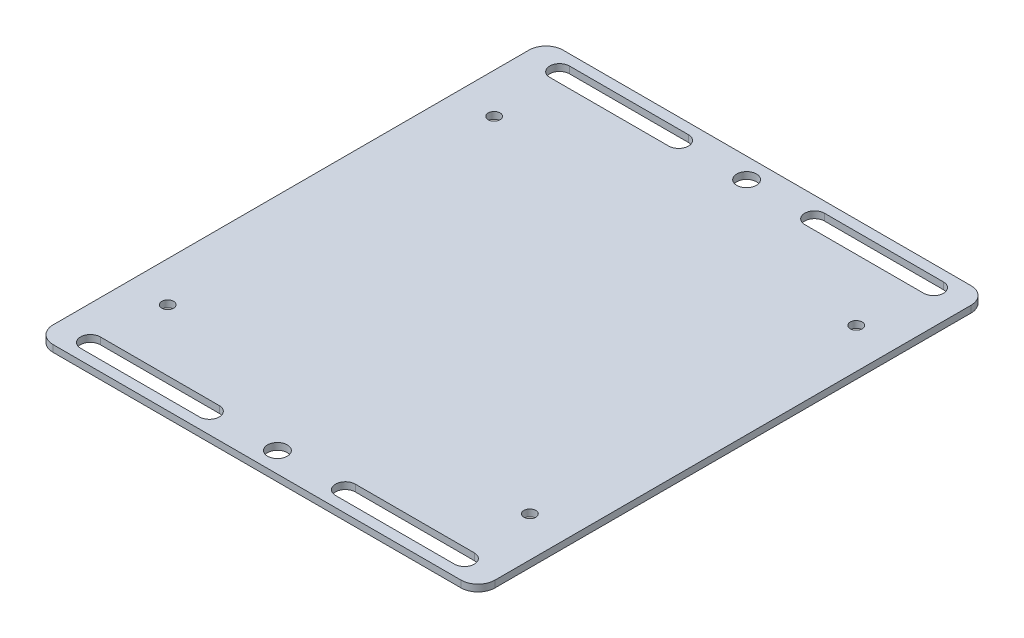
SolidWorks part; units mm, degrees
ref_plane "Front Plane" through (0, 0, 0) normal (0, 0, 1) x (1, 0, 0)
ref_plane "Top Plane" through (0, 0, 0) normal (0, 1, 0) x (1, 0, 0)
ref_plane "Right Plane" through (0, 0, 0) normal (1, 0, 0) x (0, 0, -1)
sketch "Sketch1" plane through (0, 0, 0) normal (0, 1, 0) x (1, 0, 0)
  line L1 (-57.5, 52.05) -> (57.5, 52.05) construction
  line L2 (-57.5, 52.05) -> (-57.5, -52.05) construction
  line L3 (-57.5, -52.05) -> (57.5, -52.05) construction
  line L4 (57.5, 52.05) -> (57.5, -52.05) construction
  line L5 (-57.5, 52.05) -> (57.5, -52.05) construction
  line L6 (-57.5, -52.05) -> (57.5, 52.05) construction
  line L7 (-65, -75) -> (65, -75)
  line L8 (-65, -75) -> (-65, 75)
  line L9 (-65, 75) -> (65, 75)
  line L10 (65, -75) -> (65, 75)
  line L11 (-65, -75) -> (65, 75) construction
  line L12 (-65, 75) -> (65, -75) construction
  point P0 (0, 0)
  point P6 (0, 0)
  dimension "D1" = 115
  dimension "D2" = 104.1
  dimension "D3" = 150
  dimension "D4" = 130
extrude "Boss-Extrude1" add sketch "Sketch1" along normal blind 2
sketch "Sketch2" plane through (0, 2, 0) normal (0, 1, 0) x (1, 0, 0)
  line L0 (-65, 69) -> (65, 69) construction
  line L1 (-65, 75) -> (-65, -75) construction
  line L2 (65, -75) -> (65, 75) construction
  line L3 (65, 75) -> (-65, 75) construction
  line L4 (-55, 69) -> (-20, 69) construction
  line L5 (-55, 71.9) -> (-20, 71.9)
  line L6 (-55, 66.1) -> (-20, 66.1)
  line L7 (20, 69) -> (55, 69) construction
  line L8 (20, 71.9) -> (55, 71.9)
  line L9 (20, 66.1) -> (55, 66.1)
  arc A0 (-55, 71.9) -> (-55, 66.1) centre (-55, 69) ccw
  arc A1 (-20, 66.1) -> (-20, 71.9) centre (-20, 69) ccw
  circle A2 centre (0, 69) radius 2.9
  arc A3 (20, 71.9) -> (20, 66.1) centre (20, 69) ccw
  arc A4 (55, 66.1) -> (55, 71.9) centre (55, 69) ccw
  point P10 (-37.5, 69)
  point P15 (0, 69)
  point P20 (37.5, 69)
  dimension "D2" = 5.8
  dimension "D1" = 6
  dimension "D3" = 10
  dimension "D4" = 20
  dimension "D5" = 20
  dimension "D6" = 10
extrude "Cut-Extrude1" cut sketch "Sketch2" against normal through all
mirror "Mirror1" about plane through (0, 0, 0) normal (0, 0, 1) of "Cut-Extrude1"
fillet "Fillet1" radius 5 4 edges at (65, 1, 75) (-65, 1, 75) (-65, 1, -75) (65, 1, -75)
sketch "Sketch4" plane through (0, 2, 0) normal (0, 1, 0) x (1, 0, 0)
  line L1 (-53.25, -48) -> (53.25, -48) construction
  line L2 (-53.25, -48) -> (-53.25, 48) construction
  line L3 (-53.25, 48) -> (53.25, 48) construction
  line L4 (53.25, -48) -> (53.25, 48) construction
  line L5 (-53.25, -48) -> (53.25, 48) construction
  line L6 (-53.25, 48) -> (53.25, -48) construction
  circle A0 centre (-53.25, 48) radius 1.75
  circle A1 centre (53.25, 48) radius 1.75
  circle A2 centre (-53.25, -48) radius 1.75
  circle A3 centre (53.25, -48) radius 1.75
  point P0 (0, 0)
  dimension "D3" = 3.5
  dimension "D1" = 96
  dimension "D2" = 106.5
extrude "Cut-Extrude2" cut sketch "Sketch4" against normal through all
equation "\"D5@Sketch2\"=\"D4@Sketch2\""
